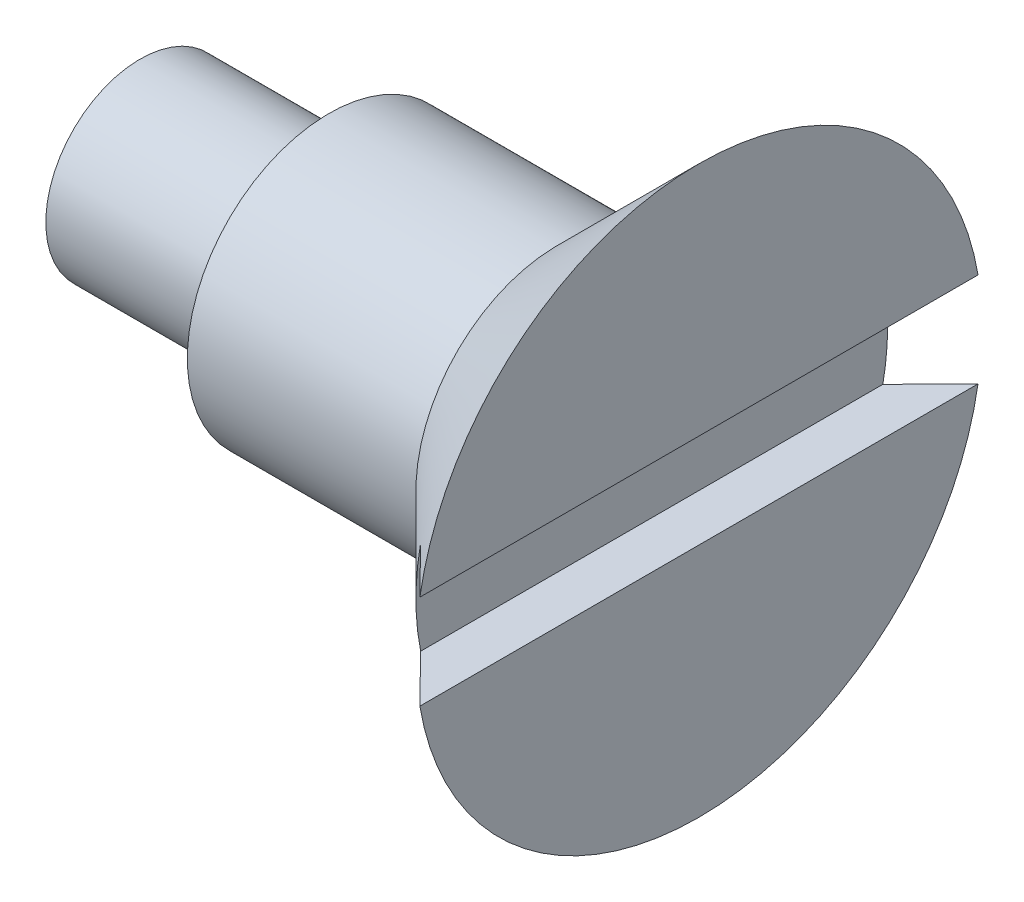
SolidWorks part; units mm, degrees
ref_plane "Front Plane" through (0, 0, 0) normal (0, 0, 1) x (1, 0, 0)
ref_plane "Top Plane" through (0, 0, 0) normal (0, 1, 0) x (1, 0, 0)
ref_plane "Right Plane" through (0, 0, 0) normal (1, 0, 0) x (0, 0, -1)
sketch "Sketch1" plane through (0, 0, 0) normal (0, 1, 0) x (1, 0, 0)
  line L0 (0, 0) -> (0, 11662.0861) construction
  line L1 (0, 0) -> (11662.0861, 0) construction
  line L4 (-3, -3) -> (0, -6)
  line L5 (0, -6) -> (0, 0)
  line L6 (0, 0) -> (-13, 0)
  line L7 (-3, -3) -> (-7.8453, -3)
  line L8 (-7.8453, -3) -> (-7.8453, -2)
  line L9 (-7.8453, -2) -> (-11.8453, -2)
  line L10 (-11.8453, -2) -> (-13, 0)
  point P10 (-8.4071, -4.2979)
  dimension "D1" = 13
  dimension "D2" = 45
  dimension "D3" = 3
  dimension "D4" = 4
  dimension "D5" = 4
  dimension "D6" = 60
  dimension "D7" = 6
revolve "Revolve1" add sketch "Sketch1" angle 360 about L6
sketch "Sketch2" plane through (0, 0, 0) normal (1, 0, 0) x (0, 0, -1)
  line L1 (-8.119, 1) -> (8.119, 1)
  line L2 (-8.119, 1) -> (-8.119, -1)
  line L3 (-8.119, -1) -> (8.119, -1)
  line L4 (8.119, 1) -> (8.119, -1)
  line L5 (-8.119, 1) -> (8.119, -1) construction
  line L6 (-8.119, -1) -> (8.119, 1) construction
  point P1 (0, 0)
  dimension "D1" = 2
extrude "Cut-Extrude1" cut sketch "Sketch2" against normal blind 1
